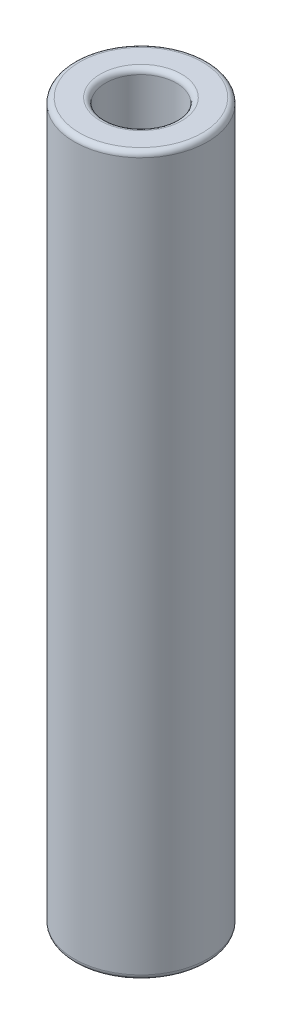
SolidWorks part; units mm, degrees
ref_plane "Front Plane" through (0, 0, 0) normal (0, 0, 1) x (1, 0, 0)
ref_plane "Top Plane" through (0, 0, 0) normal (0, 1, 0) x (1, 0, 0)
ref_plane "Right Plane" through (0, 0, 0) normal (1, 0, 0) x (0, 0, -1)
sketch "Sketch1" plane through (0, 0, 0) normal (0, 1, 0) x (1, 0, 0)
  circle A0 centre (0, 0) radius 1.7
  circle A1 centre (0, 0) radius 3.2
  dimension "D1" = 3.4
  dimension "D2" = 6.4
extrude "Boss-Extrude1" add sketch "Sketch1" along normal blind 34.5
fillet "Fillet1" radius 0.25 4 edges at (0, 0, 3.2) (0, 34.5, 3.2) (0, 0, 1.7) (0, 34.5, 1.7)
